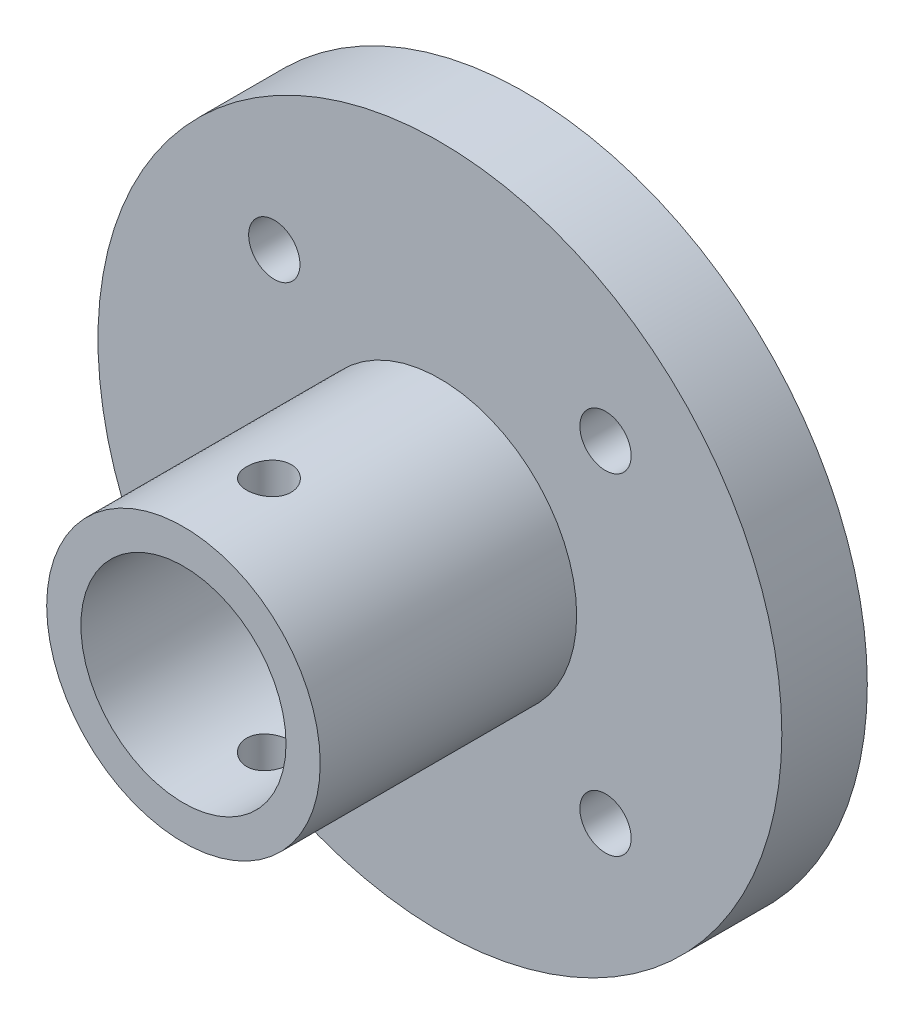
SolidWorks part; units mm, degrees
ref_plane "Front Plane" through (0, 0, 0) normal (0, 0, 1) x (1, 0, 0)
ref_plane "Top Plane" through (0, 0, 0) normal (0, 1, 0) x (1, 0, 0)
ref_plane "Right Plane" through (0, 0, 0) normal (1, 0, 0) x (0, 0, -1)
sketch "Sketch1" plane through (0, 0, 0) normal (0, 0, 1) x (1, 0, 0)
  line L0 (0, 0) -> (0, 20) construction
  line L1 (0, 20) -> (0, 0) construction
  line L2 (0, 0) -> (-20, 0) construction
  line L3 (0, 0) -> (-14.1421, 14.1421) construction
  circle A0 centre (0, 0) radius 6
  circle A1 centre (0, 0) radius 20
  circle A2 centre (-9.6862, 9.6862) radius 1.5
  circle A3 centre (9.6862, 9.6862) radius 1.5
  circle A4 centre (9.6862, -9.6862) radius 1.5
  circle A5 centre (-9.6862, -9.6862) radius 1.5
  dimension "D1" = 12
  dimension "D2" = 40
  dimension "D3" = 3
extrude "Boss-Extrude1" add sketch "Sketch1" along normal blind 5
sketch "Sketch2" plane through (0, 0, 5) normal (0, 0, 1) x (1, 0, 0)
  circle A1 centre (0, 0) radius 6
  circle A2 centre (0, 0) radius 8
  dimension "D1" = 16
extrude "Boss-Extrude2" add sketch "Sketch2" along normal blind 15
sketch "Sketch3" plane through (0, 0, 0) normal (0, 1, 0) x (1, 0, 0)
  line L0 (0, -5) -> (0, -22.7914) construction
  line L1 (-8, -5) -> (8, -5) construction
  line L2 (-8, -20) -> (11.7824, -20) construction
  circle A0 centre (0, -15) radius 1.3019
  dimension "D1" = 5
extrude "Cut-Extrude1" cut sketch "Sketch3" against normal through all both and the other way through all
